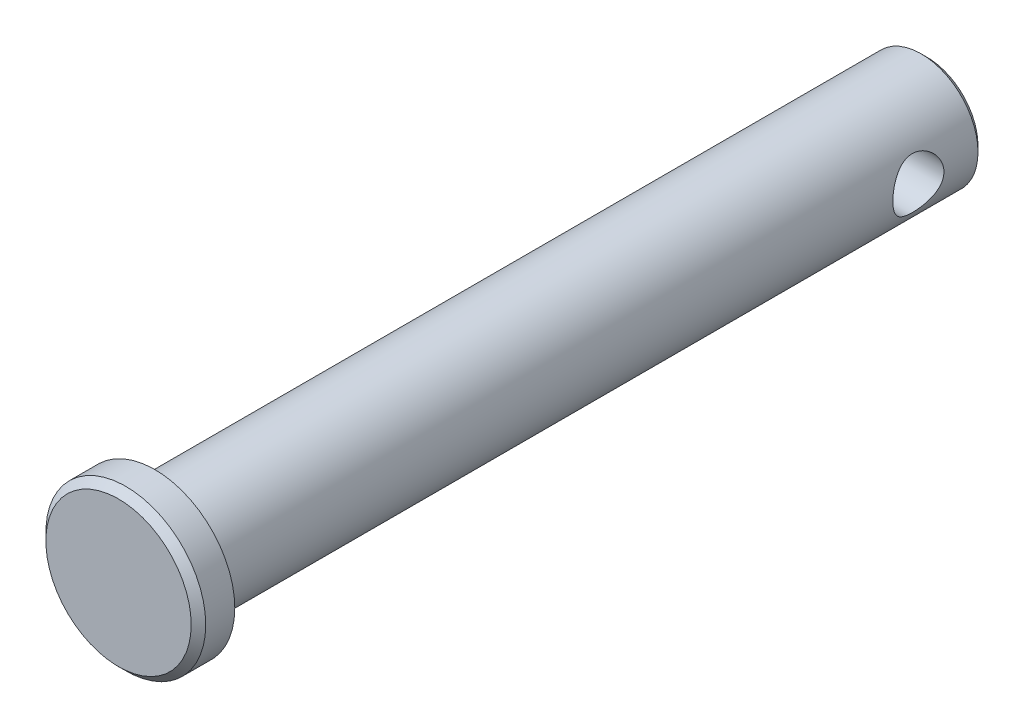
SolidWorks part; units mm, degrees
material "Alloy Steel"
ref_plane "Front" through (0, 0, 0) normal (0, 0, 1) x (1, 0, 0)
ref_plane "Top" through (0, 0, 0) normal (0, 1, 0) x (1, 0, 0)
ref_plane "Right" through (0, 0, 0) normal (1, 0, 0) x (0, 0, -1)
sketch "Sketch1" plane through (0, 0, 0) normal (0, 0, 1) x (1, 0, 0)
  circle A0 centre (0, 0) radius 3.9688
  point P3 (0, 3.9688)
  point P4 (0, -3.9688)
  dimension "dia" = 7.9375
extrude "Extrude1" add sketch "Sketch1" along normal mid plane 53.975
sketch "Sketch2" plane through (0, 0, 26.9875) normal (0, 0, 1) x (1, 0, 0)
  circle A0 centre (0, 0) radius 5.588
  dimension "head dia" = 11.176
extrude "Extrude2" add sketch "Sketch2" along normal blind 2.54
chamfer "Chamfer1" distance 0.508 angle 45 1 edges at (5.588, 0, 29.5275)
sketch "Sketch3" plane through (0, 0, 0) normal (1, 0, 0) x (0, 0, -1)
  line L0 (-26.9875, -3.9688) -> (-26.9875, 3.9688) construction
  circle A0 centre (22.4234, 0) radius 1.7859
  point P2 (20.6375, 0)
  dimension "hole dia" = 3.5719
  dimension "useable Lg" = 47.625
extrude "Extrude3" cut sketch "Sketch3" against normal through all and the other way through all
chamfer "Chamfer2" distance 0.3969 angle 45 1 edges at (3.9688, 0, -26.9875)
ref_plane "Plane1" through (0, 0, -22.4234) normal (0, 0, 1) x (1, 0, 0)
sketch "Sketch8" plane through (0, 0, 0) normal (1, 0, 0) x (0, 0, -1)
  line L0 (-29.5275, 5.08) -> (-29.5275, -5.08) construction
  line L1 (-29.0195, -5.588) -> (-26.9875, -5.588) construction
  line L2 (26.9875, -3.5719) -> (26.9875, 3.5719) construction
  point P0 (-29.5275, 5.588)
  point P1 (-26.9875, 5.588)
  point P5 (26.9875, 3.9688)
  point P8 (-29.5275, -5.588)
  point P9 (26.9875, -3.9688)
equation "\"D1@Chamfer1\" = \"head ht@Extrude2\" * .2"
equation "\"D1@Chamfer2\" = \"dia@Sketch1\" * .05"
